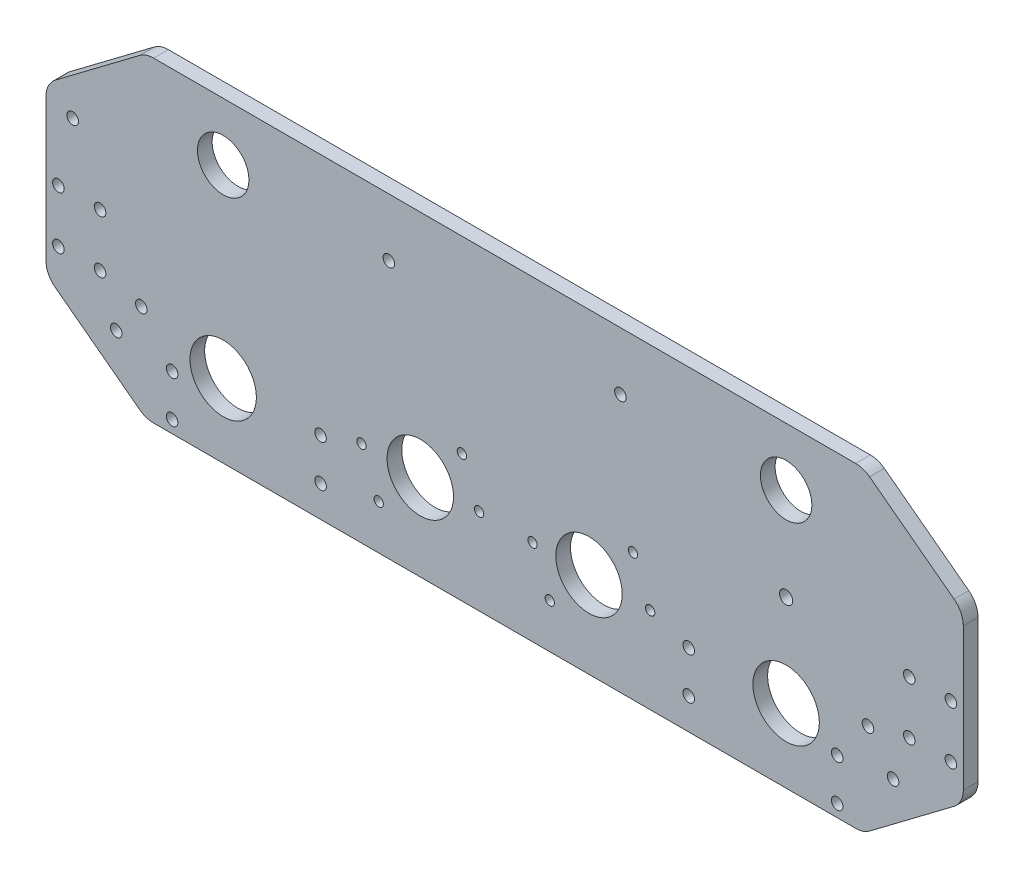
SolidWorks part; units mm, degrees
other "Marca1"
sketch "Croquis7" plane through (-185.6263, 143.9, 0) normal (-0.9207, 0.3803, -0.0878) x (0.0129, 0.2544, 0.967)
material "6061-O (SS)"
ref_plane "Alzado" through (0, 0, 0) normal (0, 0, 1) x (1, 0, 0)
ref_plane "Planta" through (0, 0, 0) normal (0, 1, 0) x (1, 0, 0)
ref_plane "Vista lateral" through (0, 0, 0) normal (1, 0, 0) x (0, 0, -1)
sketch "Croquis1" plane through (0, 0, 0) normal (0, 0, 1) x (1, 0, 0)
  line L0 (155, 0) -> (-155, 0)
  line L1 (-155, 0) -> (-198.1263, 32.498)
  line L2 (0, 127.4112) -> (0, -127.4112) construction
  line L3 (-198.1263, 32.498) -> (-198.1263, 104.0239)
  line L5 (-123.3669, 68.261) -> (123.3669, 68.261)
  line L6 (155, 0) -> (198.1263, 32.498)
  line L7 (198.1263, 32.498) -> (198.1263, 104.0239)
  line L9 (-155, 68.261) -> (-123.3669, 0) construction
  line L10 (-155, 0) -> (-123.3669, 0)
  line L11 (-155, 0) -> (-155, 68.261)
  line L12 (-155, 68.261) -> (-123.3669, 68.261)
  line L13 (-123.3669, 0) -> (-123.3669, 68.261)
  line L14 (-155, 0) -> (-123.3669, 68.261) construction
  line L15 (-155, 68.261) -> (-198.1263, 68.261)
  line L16 (123.3669, 68.261) -> (198.1263, 68.261)
  line L17 (155, 136.5219) -> (198.1263, 104.0239)
  line L18 (155, 136.5219) -> (-155, 136.5219)
  line L19 (-155, 136.5219) -> (-198.1263, 104.0239)
  point P4 (0, 0)
  point P9 (0, 0)
  point P13 (0, 68.261)
  dimension "D1" = 310
  dimension "D2" = 143
  dimension "D3" = 32.498
  dimension "D4" = 71.5259
extrude "Saliente-Extruir1" add sketch "Croquis1" along normal blind 6.35
sketch "Croquis2" plane through (0, 0, 6.35) normal (0, 0, 1) x (1, 0, 0)
  line L0 (0, 0) -> (0, 68.261) construction
  line L1 (-155, 0) -> (-97.6848, 0) construction
  line L4 (-198.1263, 32.498) -> (-198.1263, 104.0239) construction
  line L5 (155, 0) -> (-155, 0) construction
  line L13 (-90.6044, 57.15) -> (-152.5804, 57.15)
  line L14 (-90.6044, 57.15) -> (-90.6044, 6.35)
  line L15 (-90.6044, 6.35) -> (-152.5804, 6.35)
  line L16 (-152.5804, 57.15) -> (-152.5804, 6.35)
  line L17 (-90.6044, 57.15) -> (-152.5804, 6.35) construction
  line L18 (-90.6044, 6.35) -> (-152.5804, 57.15) construction
  circle A0 centre (-121.5924, 31.75) radius 14.345
  circle A1 centre (121.5924, 31.75) radius 14.345
  circle A4 centre (-51.5924, 45.4) radius 45.5 construction
  circle A5 centre (-51.5924, 45.4) radius 4.8593
  point P6 (-121.5924, 31.75)
  dimension "D1" = 28.69
  dimension "D3" = 91
  dimension "D4" = 76.5339
  dimension "D5" = 70
  dimension "D2" = 61.976
  dimension "D6" = 45.4
  dimension "D7" = 31.75
  dimension "D8" = 31.75
  dimension "D9" = 50.8
  dimension "D10" = 33.4076
fillet "Redondeo1" radius 10 8 edges at (-198.1263, 32.498, 3.175) (198.1263, 32.498, 3.175) (155, 0, 3.175) (-155, 0, 3.175) (155, 136.5219, 3.175) (198.1263, 104.0239, 3.175) (-155, 136.5219, 3.175) (-198.1263, 104.0239, 3.175)
extrude "Cortar-Extruir1" cut sketch "Croquis2" against normal blind 10 contours A0 | A1
sketch "Croquis3" plane through (0, 0, 6.35) normal (0, 0, 1) x (1, 0, 0)
  line L0 (-50.0924, 67.9) -> (-50.0924, 105.9) construction
  circle A0 centre (-50.0924, 45.4) radius 22.5 construction
  circle A2 centre (-50.0924, 105.9) radius 36.5
  circle A3 centre (-50.0924, 105.9) radius 38
  dimension "D1" = 45
  dimension "D3" = 73
  dimension "D2" = 38
sketch "Croquis8" plane through (0, 0, 6.35) normal (0, 0, 1) x (1, 0, 0)
  line L0 (151.654, 0) -> (-151.654, 0) construction
  line L1 (-63.4934, 74.4) -> (-9.3914, 74.4) construction
  line L2 (-63.4934, 74.4) -> (-63.4934, 0) construction
  line L3 (-63.4934, 0) -> (-9.3914, 0) construction
  line L4 (-9.3914, 74.4) -> (-9.3914, 0) construction
  line L5 (-63.4934, 74.4) -> (-9.3914, 0) construction
  line L6 (0, 0) -> (0, 136.5219) construction
  line L7 (151.654, 136.5219) -> (-151.654, 136.5219) construction
  line L8 (-61.8424, 37.2) -> (-11.0424, 37.2) construction
  line L9 (-54.4029, 19.2395) -> (-18.4819, 55.1605) construction
  circle A1 centre (-36.4424, 37.2) radius 37 construction
  circle A2 centre (-36.4424, 37.2) radius 14.345
  circle A3 centre (36.4424, 37.2) radius 14.345
  circle A4 centre (-36.4424, 37.2) radius 25.4 construction
  circle A10 centre (12.0572, 37.2) radius 2.01
  circle A11 centre (19.4967, 19.2395) radius 2.01
  circle A12 centre (62.8572, 37.2) radius 2.01
  circle A13 centre (55.4177, 55.1605) radius 2.01
  circle A14 centre (-18.4819, 55.1605) radius 2.02
  circle A15 centre (-11.0424, 37.2) radius 2.02
  circle A16 centre (-54.4029, 19.2395) radius 2.02
  circle A17 centre (-61.8424, 37.2) radius 2.02
  circle A18 centre (-121.5924, 31.75) radius 14.345
  point P20 (-36.4424, 37.2)
  point P23 (-36.4424, 37.2)
  dimension "D1" = 54.102
  dimension "D3" = 74
  dimension "D4" = 28.69
  dimension "D5" = 50.8
  dimension "D7" = 4.04
  dimension "D8" = 85.15
  dimension "D2" = 74.4
  dimension "D6" = 45
extrude "Cortar-Extruir2" cut sketch "Croquis8" against normal through all both and the other way through all
chamfer "Chaflán3" distance 1 angle 45 8 edges at (-52.3829, 19.2395, 0) (-59.8224, 37.2, 0) (-16.4619, 55.1605, 0) (-9.0224, 37.2, 0) (10.0472, 37.2, 0) (17.4867, 19.2395, 0) (53.4077, 55.1605, 0) (60.8472, 37.2, 0)
sketch "Croquis9" plane through (0, 0, 0) normal (0, 0, -1) x (-1, 0, 0)
  line L0 (0, 0) -> (0, 136.5219) construction
  line L1 (-151.654, 136.5219) -> (151.654, 136.5219) construction
  line L2 (-121.5924, 31.75) -> (-121.5924, 111.5219) construction
  line L3 (121.5924, 31.75) -> (121.5924, 111.5219) construction
  line L4 (-121.5924, 111.5219) -> (121.5924, 111.5219) construction
  circle A0 centre (0, 111.5219) radius 11.1125 construction
  circle A1 centre (-121.5924, 111.5219) radius 11.1125
  circle A2 centre (121.5924, 111.5219) radius 11.1125
  dimension "D1" = 22.225
  dimension "D2" = 25
  dimension "D3" = 25
  dimension "D4" = 243.1848
extrude "Cortar-Extruir3" cut sketch "Croquis9" against normal blind 10
sketch "Croquis10" plane through (0, 0, 0) normal (0, 0, -1) x (-1, 0, 0)
  line L0 (-121.5924, 111.5219) -> (121.5924, 111.5219) construction
  line L1 (0, 111.5219) -> (0, 136.5219) construction
  line L2 (-151.654, 136.5219) -> (151.654, 136.5219) construction
  line L3 (50, 111.5219) -> (50, 136.5219) construction
  line L4 (-121.5924, 111.5219) -> (-121.5924, 31.75) construction
  line L5 (121.5924, 111.5219) -> (186.5924, 111.5219) construction
  line L6 (186.5924, 111.5219) -> (186.5924, 96.5219) construction
  circle A0 centre (-50, 111.5219) radius 2.5
  circle A1 centre (50, 111.5219) radius 2.5
  circle A3 centre (-121.5924, 71.4619) radius 2.8432
  circle A4 centre (186.5924, 96.5219) radius 2.5
  dimension "D1" = 5
  dimension "D2" = 40.06
  dimension "D4" = 65
  dimension "D3" = 50
  dimension "D6" = 5
  dimension "D5" = 15
extrude "Cortar-Extruir4" cut sketch "Croquis10" against normal blind 10
sketch "Croquis11" plane through (0, 0, 6.35) normal (0, 0, 1) x (1, 0, 0)
  line L0 (-143.654, 31.85) -> (-143.654, 0) construction
  line L1 (-151.654, 0) -> (-135.654, 0) construction
  line L2 (-151.654, 0) -> (-151.654, 31.85) construction
  line L3 (-151.654, 31.85) -> (-135.654, 31.85) construction
  line L4 (-135.654, 0) -> (-135.654, 31.85) construction
  line L5 (-79.5224, 0) -> (-79.5224, 51.998) construction
  line L6 (151.654, 0) -> (-151.654, 0) construction
  line L7 (0, 0) -> (0, 136.5219) construction
  line L8 (-87.5224, 40) -> (-71.5224, 40) construction
  line L9 (-87.5224, 40) -> (-87.5224, 0) construction
  line L10 (-87.5224, 0) -> (-71.5224, 0) construction
  line L11 (-71.5224, 40) -> (-71.5224, 0) construction
  line L12 (-87.5224, 40) -> (-71.5224, 0) construction
  line L13 (-87.5224, 0) -> (-71.5224, 40) construction
  line L14 (151.654, 136.5219) -> (-151.654, 136.5219) construction
  line L15 (-198.1263, 37.4838) -> (-198.1263, 99.0381) construction
  line L16 (-198.1263, 37.4838) -> (-166.2763, 37.4838) construction
  line L17 (-198.1263, 37.4838) -> (-198.1263, 53.4838) construction
  line L18 (-198.1263, 53.4838) -> (-166.2763, 53.4838) construction
  line L19 (-166.2763, 37.4838) -> (-166.2763, 53.4838) construction
  line L20 (-166.2763, 45.4838) -> (-198.1263, 45.4838) construction
  line L21 (-198.1263, 68.261) -> (-164.4763, 68.261) construction
  line L22 (-174.7763, 45.4838) -> (-174.7763, 68.261) construction
  line L23 (-192.7763, 45.4838) -> (-192.7763, 68.261) construction
  line L24 (-175.9083, 15.7556) -> (-151.8357, 47.701) construction
  line L26 (-194.1445, 29.4975) -> (-157.6722, 2.0136) construction
  circle A0 centre (-143.654, 23.35) radius 2.5
  circle A1 centre (-143.654, 5.35) radius 2.5
  circle A2 centre (-121.5924, 31.75) radius 14.345 construction
  circle A3 centre (-36.4424, 37.2) radius 14.3149 construction
  circle A4 centre (-79.5224, 31.5) radius 2.5
  circle A5 centre (-79.5224, 13.5) radius 2.5
  circle A6 centre (143.654, 5.35) radius 2.5
  circle A7 centre (143.654, 23.35) radius 2.5
  circle A8 centre (79.5224, 13.5) radius 2.5
  circle A9 centre (79.5224, 31.5) radius 2.5
  arc A10 (-198.1263, 37.4838) -> (-194.1445, 29.4975) centre (-188.1263, 37.4838) ccw construction
  circle A11 centre (-174.7763, 45.4838) radius 2.5
  circle A12 centre (-192.7763, 45.4838) radius 2.5
  circle A13 centre (-174.7763, 68.261) radius 2.5
  circle A14 centre (-192.7763, 68.261) radius 2.5
  circle A15 centre (174.7763, 45.4838) radius 2.5
  circle A16 centre (192.7763, 45.4838) radius 2.5
  circle A17 centre (192.7763, 68.261) radius 2.5
  circle A18 centre (174.7763, 68.261) radius 2.5
  circle A23 centre (-156.9512, 40.9126) radius 2.5
  circle A24 centre (-167.7838, 26.5371) radius 2.5
  circle A25 centre (167.7838, 26.5371) radius 2.5
  circle A26 centre (156.9512, 40.9126) radius 2.5
  point P21 (-79.5224, 20)
  dimension "D3" = 5
  dimension "D4" = 8.5
  dimension "D5" = 18
  dimension "D6" = 85.15
  dimension "D10" = 8.5
  dimension "D11" = 18
  dimension "D14" = 5
  dimension "D15" = 8.5
  dimension "D16" = 18
  dimension "D17" = 5
  dimension "D18" = 5
  dimension "D19" = 5
  dimension "D22" = 5
  dimension "D23" = 8.5
  dimension "D24" = 18
  dimension "D21" = 5
  dimension "D1" = 31.85
  dimension "D2" = 16
  dimension "D7" = 42.07
  dimension "D8" = 40
  dimension "D9" = 16
  dimension "D12" = 16
  dimension "D13" = 31.85
  dimension "D20" = 40
extrude "Cortar-Extruir5" cut sketch "Croquis11" against normal blind 10
